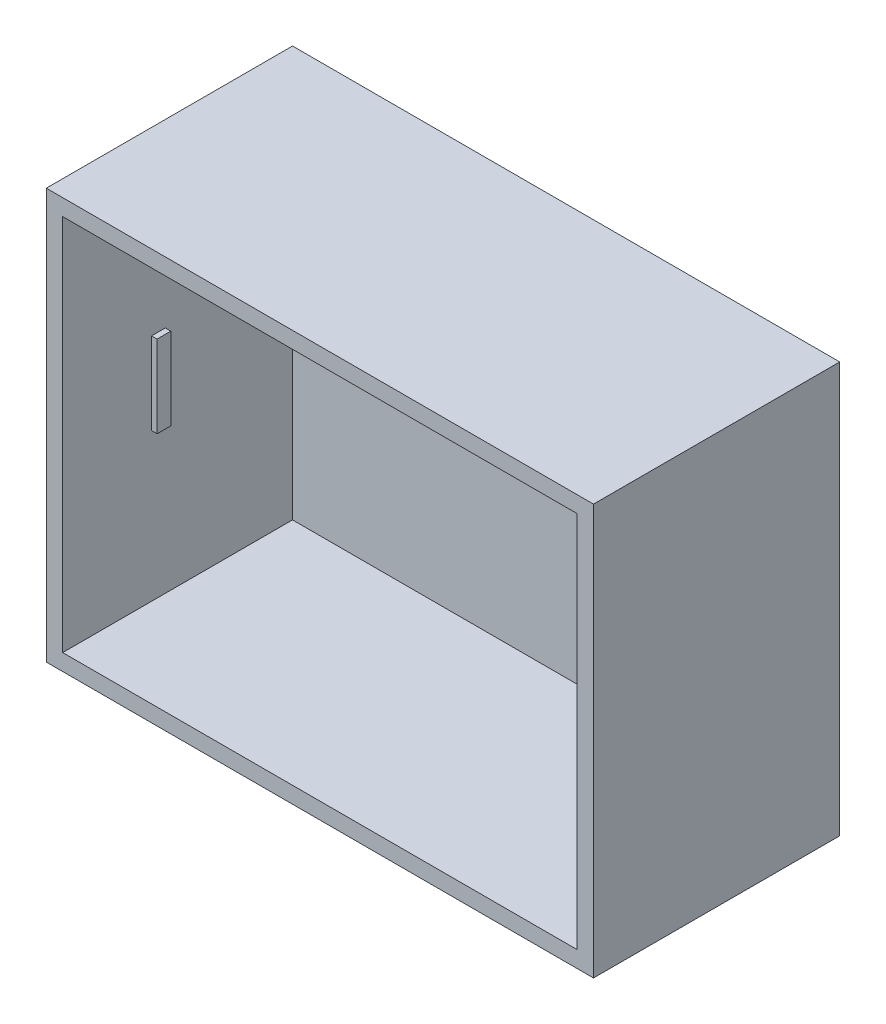
SolidWorks part; units mm, degrees
ref_plane "Front Plane" through (0, 0, 0) normal (0, 0, 1) x (1, 0, 0)
ref_plane "Top Plane" through (0, 0, 0) normal (0, 1, 0) x (1, 0, 0)
ref_plane "Right Plane" through (0, 0, 0) normal (1, 0, 0) x (0, 0, -1)
other "Configuration Table"
sketch "Sketch2" plane through (0, 0, 0) normal (0, 0, 1) x (1, 0, 0)
  line L1 (-40, -30) -> (40, -30)
  line L2 (-40, -30) -> (-40, 30)
  line L3 (-40, 30) -> (40, 30)
  line L4 (40, -30) -> (40, 30)
extrude "Floor_2p4" add sketch "Sketch2" along normal blind 2.4 from offset 0
sketch "Sketch3" plane through (0, 0, 0) normal (0, 0, 1) x (1, 0, 0)
  line L1 (-40, -30) -> (40, -30)
  line L2 (-40, -30) -> (-40, 30)
  line L3 (-40, 30) -> (40, 30)
  line L4 (40, -30) -> (40, 30)
  line L5 (-37.6, -27.6) -> (37.6, -27.6)
  line L6 (-37.6, -27.6) -> (-37.6, 27.6)
  line L7 (-37.6, 27.6) -> (37.6, 27.6)
  line L8 (37.6, -27.6) -> (37.6, 27.6)
extrude "Walls_2p4" add sketch "Sketch3" along normal blind 33.6 from offset 2.4
sketch "Sketch4" plane through (0, 0, 0) normal (0, 0, 1) x (1, 0, 0)
  line L0 (-37.6, 27.6) -> (-37.6, -27.6) construction
  line L1 (-37.6, -6) -> (-36.8, -6)
  line L2 (-37.6, -6) -> (-37.6, 6)
  line L3 (-37.6, 6) -> (-36.8, 6)
  line L4 (-36.8, -6) -> (-36.8, 6)
extrude "Catch_left" add sketch "Sketch4" along normal blind 2 from offset 21
sketch "Sketch5" plane through (0, 0, 0) normal (0, 0, 1) x (1, 0, 0)
  line L0 (37.6, -27.6) -> (37.6, 27.6) construction
  line L1 (36.8, -6) -> (37.6, -6)
  line L2 (36.8, -6) -> (36.8, 6)
  line L3 (36.8, 6) -> (37.6, 6)
  line L4 (37.6, -6) -> (37.6, 6)
extrude "Catch_right" add sketch "Sketch5" along normal blind 2 from offset 21
